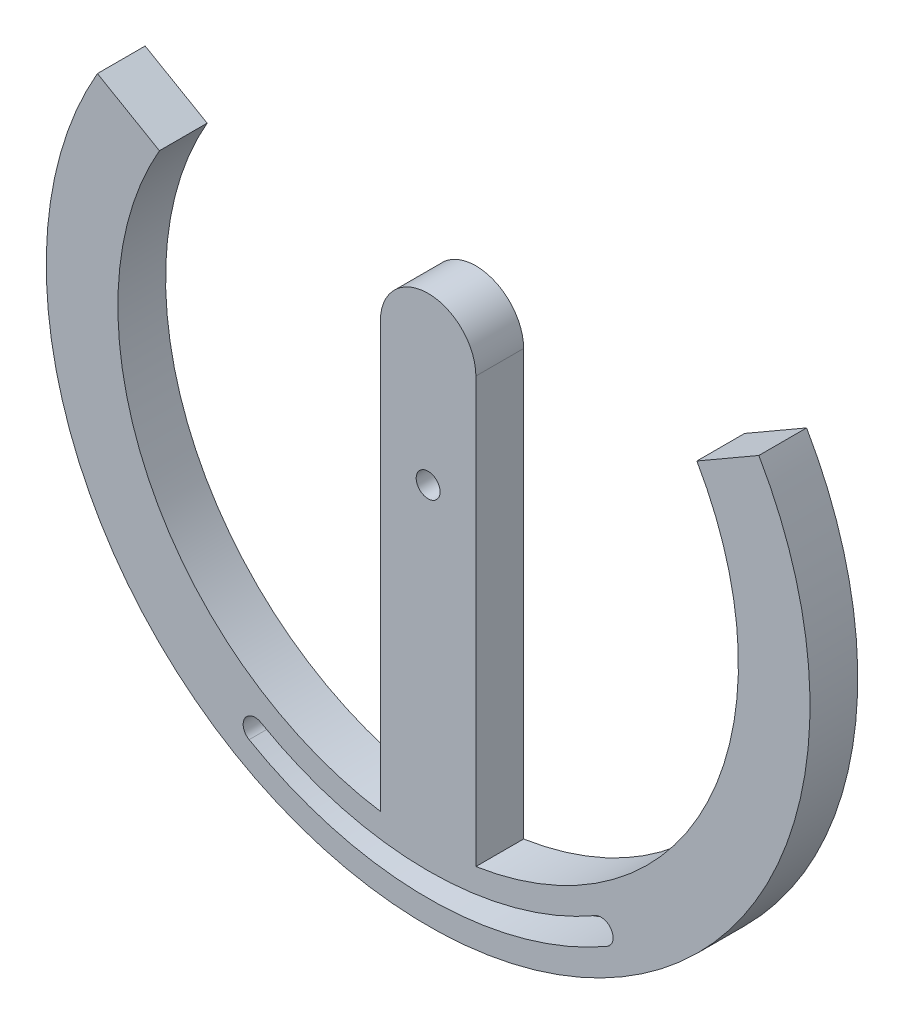
SolidWorks part; units mm, degrees
material "Brass"
ref_plane "Front Plane" through (0, 0, 0) normal (0, 0, 1) x (1, 0, 0)
ref_plane "Top Plane" through (0, 0, 0) normal (0, 1, 0) x (1, 0, 0)
ref_plane "Right Plane" through (0, 0, 0) normal (1, 0, 0) x (0, 0, -1)
sketch "Sketch1" plane through (0, 0, 0) normal (0, 0, 1) x (1, 0, 0)
  line L0 (68.3024, 39.4344) -> (43369.5726, 25039.4344) construction
  line L1 (-57.2402, 33.0476) -> (-43358.5104, 25033.0476) construction
  line L2 (-1000, 0) -> (49000, 0) construction
  line L3 (0, -1000) -> (0, 49000) construction
  line L4 (0, 0) -> (-28678.8218, 40957.6022) construction
  line L5 (0, 0) -> (28678.8218, 40957.6022) construction
  line L6 (-131.9823, 76.2) -> (-32.9956, 19.05) construction
  circle A0 centre (0, 0) radius 101.6
  dimension "D1" = 203.2
extrude "Extrude1" add sketch "Sketch1" along normal blind 12.7
sketch "Sketch3" plane through (0, 0, 12.7) normal (0, 0, 1) x (1, 0, 0)
  line L0 (3.175, -5.4993) -> (-24996.825, 43295.7709) construction
  line L1 (-3.175, -5.4993) -> (24996.825, 43295.7709) construction
  circle A0 centre (0, 0) radius 3.175
  arc A1 (47.625, -82.4889) -> (-47.625, -82.4889) centre (0, 0) cw
  arc A2 (44.45, -76.9897) -> (-44.45, -76.9897) centre (0, 0) cw
  circle A3 centre (0, 0) radius 101.6 construction
  arc A4 (-47.625, -82.4889) -> (-44.45, -76.9897) centre (-46.0375, -79.7393) cw
  arc A5 (44.45, -76.9897) -> (47.625, -82.4889) centre (46.0375, -79.7393) cw
  dimension "D1" = 6.35
  dimension "D2" = 6.35
  dimension "D3" = 6.35
extrude "Extrude3" cut sketch "Sketch3" against normal through all
sketch "Sketch4" plane through (0, 0, 12.7) normal (0, 0, 1) x (1, 0, 0)
  line L0 (0, 0) -> (-12940.9523, -48296.2913) construction
  line L1 (0, 0) -> (12940.9523, -48296.2913) construction
  line L2 (0, 0) -> (-43301.2702, 25000) construction
  line L3 (0, 0) -> (43301.2702, 25000) construction
  line L4 (-12.7, -982.2937) -> (-12.7, 49017.7063) construction
  line L5 (12.7, -980.1256) -> (12.7, 49019.8744) construction
  line L6 (-87.9882, 50.8) -> (-71.4904, 41.275)
  line L7 (71.4904, 41.275) -> (87.9882, 50.8)
  line L8 (-12.7, 31.4504) -> (-12.7, -81.5672)
  line L9 (12.7, 31.4504) -> (12.7, -81.5672)
  arc A0 (-87.9882, 50.8) -> (87.9882, 50.8) centre (0, 0) ccw
  arc A1 (12.7, 31.4504) -> (-12.7, 31.4504) centre (0, 31.4504) ccw
  circle A3 centre (0, 0) radius 101.6 construction
  arc A4 (71.4904, 41.275) -> (12.7, -81.5672) centre (0, 0) cw
  arc A5 (-71.4904, 41.275) -> (-12.7, -81.5672) centre (0, 0) ccw
  dimension "D1" = 12.7
  dimension "D2" = 12.7
  dimension "D3" = 82.55
  dimension "D4" = 82.55
extrude "Extrude4" cut sketch "Sketch4" against normal through all flip side to cut
equation "\"D1@Sketch3\" = \"D1@Sketch1\"*3/8"
equation "\"D1@Sketch4\"=\"D1@Sketch1\"*3/4"
